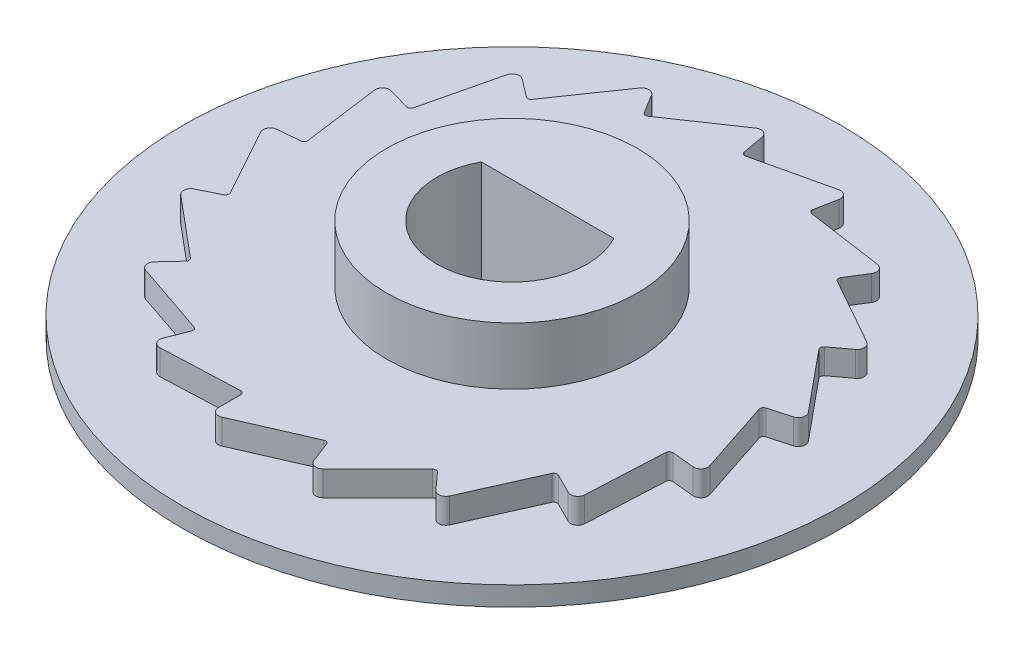
SolidWorks part; units mm, degrees
material "2014 Alloy"
ref_plane "Front Plane" through (0, 0, 0) normal (0, 0, 1) x (1, 0, 0)
ref_plane "Top Plane" through (0, 0, 0) normal (0, 1, 0) x (1, 0, 0)
ref_plane "Right Plane" through (0, 0, 0) normal (1, 0, 0) x (0, 0, -1)
sketch "Sketch1" plane through (0, 0, 0) normal (0, 1, 0) x (1, 0, 0)
  circle A0 centre (0, 0) radius 58.42
  dimension "D1" = 116.84
extrude "Boss-Extrude1" add sketch "Sketch1" along normal blind 3.429
sketch "Sketch2" plane through (0, 3.429, 0) normal (0, 1, 0) x (1, 0, 0)
  circle A0 centre (0, 0) radius 47.7006
  dimension "D1" = 95.4013
extrude "Boss-Extrude3" add sketch "Sketch2" along normal blind 4.445
sketch "Sketch4" plane through (0, 7.874, 0) normal (0, 1, 0) x (1, 0, 0)
  line L0 (-1.27, 47.6837) -> (0, 40.64)
  line L1 (0, 40.64) -> (17.0079, 44.5655)
  circle A0 centre (0, 0) radius 47.7006 construction
  arc A1 (-1.27, 47.6837) -> (17.0079, 44.5655) centre (0, 0) cw
  dimension "D4" = 47.7006
  dimension "D1" = 1.27
  dimension "D2" = 18.542
  dimension "D3" = 40.64
extrude "Cut-Extrude2" cut sketch "Sketch4" against normal up to surface (4.445 mm away) up to face at (0, 3.429, 47.7006)
pattern_circular "CirPattern1" count 17 over 360 about axis through (0, 0, 0) along (0, 1, 0) of "Cut-Extrude2"
fillet "Fillet1" radius 1.27 17 edges at (-18.0873, 5.6515, -43.4769) (-32.5716, 5.6515, -34.0072) (-42.6569, 5.6515, -19.9445) (-46.9812, 5.6515, -3.1882) (-44.9604, 5.6515, 13.9986) (-36.8674, 5.6515, 29.2949) (-23.7953, 5.6515, 40.6347) (-7.5095, 5.6515, 46.4866) (9.7905, 5.6515, 46.0602) (25.7682, 5.6515, 39.4131) (38.2658, 5.6515, 27.4431) (45.5954, 5.6515, 11.7667) (46.7671, 5.6515, -5.4988) (41.6226, 5.6515, -22.0217) (30.8568, 5.6515, -35.5704) (15.9235, 5.6515, -44.3152) (-1.1602, 5.6515, -47.0749)
fillet "Fillet2" radius 0.635 17 edges at (7.4676, 5.6515, 39.948) (21.3942, 5.6515, 34.5528) (32.4314, 5.6515, 24.4911) (39.0886, 5.6515, 11.1217) (40.4666, 5.6515, -3.7498) (36.3794, 5.6515, -18.1148) (27.379, 5.6515, -30.0333) (14.6809, 5.6515, -37.8957) (0, 5.6515, -40.64) (-14.6809, 5.6515, -37.8957) (-27.379, 5.6515, -30.0333) (-36.3794, 5.6515, -18.1148) (-40.4666, 5.6515, -3.7498) (-39.0886, 5.6515, 11.1217) (-32.4314, 5.6515, 24.4911) (-21.3942, 5.6515, 34.5528) (-7.4676, 5.6515, 39.948)
sketch "Sketch5" plane through (0, 7.874, 0) normal (0, 1, 0) x (1, 0, 0)
  circle A0 centre (0, 0) radius 22.225
  dimension "D1" = 44.45
extrude "Boss-Extrude4" add sketch "Sketch5" along normal blind 10.16
sketch "Sketch6" plane through (0, 18.034, 0) normal (0, 1, 0) x (1, 0, 0)
  line L0 (-11.7475, 6.3102) -> (11.7475, 6.3102)
  arc A0 (-11.7475, 6.3102) -> (11.7475, 6.3102) centre (0, 0) ccw
  dimension "D1" = 26.67
  dimension "D2" = 23.495
extrude "Cut-Extrude3" cut sketch "Sketch6" against normal through all
sketch "Sketch7" plane through (0, 0, 0) normal (0, -1, 0) x (1, 0, 0)
  circle A0 centre (0, 0) radius 19.05
  circle A1 centre (0, 0) radius 20.32
  dimension "D1" = 38.1
  dimension "D2" = 40.64
extrude "Cut-Extrude4" cut sketch "Sketch7" against normal blind 10.16 contours A0 | A1
